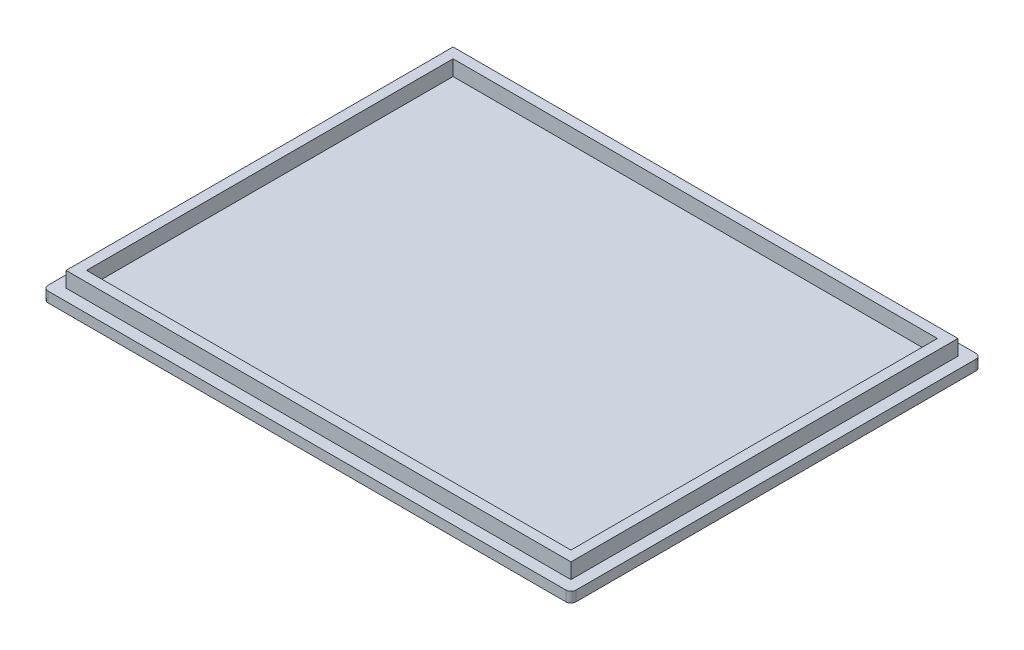
SolidWorks part; units mm, degrees
ref_plane "Front Plane" through (0, 0, 0) normal (0, 0, 1) x (1, 0, 0)
ref_plane "Top Plane" through (0, 0, 0) normal (0, 1, 0) x (1, 0, 0)
ref_plane "Right Plane" through (0, 0, 0) normal (1, 0, 0) x (0, 0, -1)
sketch "Sketch1" plane through (0, 0, 0) normal (0, 1, 0) x (1, 0, 0)
  line L1 (0, 0) -> (261.62, 0)
  line L2 (0, 0) -> (0, 203.2)
  line L3 (0, 203.2) -> (261.62, 203.2)
  line L4 (261.62, 0) -> (261.62, 203.2)
  dimension "D1" = 261.62
  dimension "D2" = 203.2
extrude "Boss-Extrude1" add sketch "Sketch1" along normal blind 5.08
sketch "Sketch2" plane through (0, 5.08, 0) normal (0, 1, 0) x (1, 0, 0)
  line L0 (0, 203.2) -> (0, 0) construction
  line L1 (5.715, 197.485) -> (255.905, 197.485)
  line L2 (5.715, 197.485) -> (5.715, 5.715)
  line L3 (5.715, 5.715) -> (255.905, 5.715)
  line L4 (255.905, 197.485) -> (255.905, 5.715)
  line L5 (10.795, 192.405) -> (250.825, 192.405)
  line L6 (10.795, 192.405) -> (10.795, 10.795)
  line L7 (10.795, 10.795) -> (250.825, 10.795)
  line L8 (250.825, 192.405) -> (250.825, 10.795)
  line L9 (261.62, 0) -> (261.62, 203.2) construction
  line L10 (0, 0) -> (261.62, 0) construction
  line L11 (261.62, 203.2) -> (0, 203.2) construction
  dimension "D1" = 5.715
  dimension "D2" = 5.715
  dimension "D3" = 5.715
  dimension "D4" = 5.715
  dimension "D5" = 5.08
  dimension "D6" = 5.08
  dimension "D7" = 5.08
  dimension "D8" = 5.08
extrude "Boss-Extrude2" add sketch "Sketch2" along normal blind 7.62
fillet "Fillet2" radius 2.54 4 edges at (261.62, 2.54, -203.2) (0, 2.54, -203.2) (0, 2.54, 0) (261.62, 2.54, 0)
